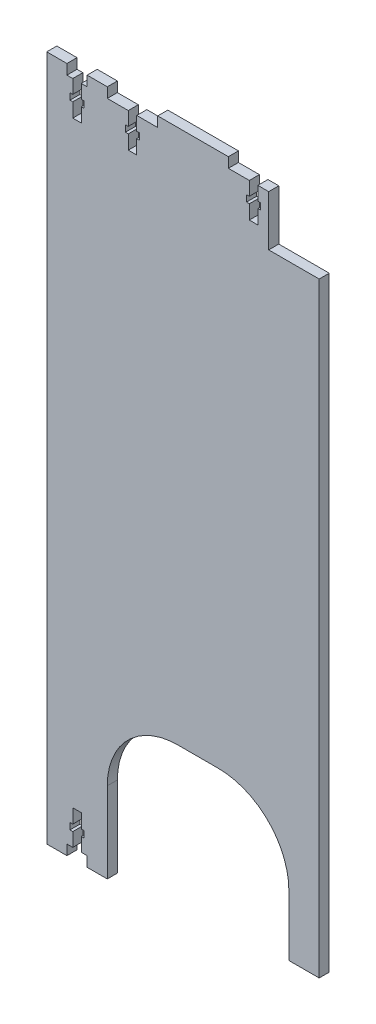
SolidWorks part; units mm, degrees
ref_plane "Front Plane" through (0, 0, 0) normal (0, 0, 1) x (1, 0, 0)
ref_plane "Top Plane" through (0, 0, 0) normal (0, 1, 0) x (1, 0, 0)
ref_plane "Right Plane" through (0, 0, 0) normal (1, 0, 0) x (0, 0, -1)
sketch "Sketch1" plane through (0, 0, 0) normal (0, 0, 1) x (1, 0, 0)
  line L0 (-100, 335) -> (-90, 335) construction
  line L1 (0, 0) -> (-110, 0)
  line L2 (0, 0) -> (0, 330)
  line L3 (0, 330) -> (-110, 330)
  line L4 (-110, 0) -> (-110, 330)
  line L5 (-110, 330) -> (-100, 330)
  line L6 (-110, 330) -> (-110, 335)
  line L7 (-110, 335) -> (-100, 335)
  line L8 (-100, 330) -> (-100, 335)
  line L9 (-90, 330) -> (-80, 330)
  line L10 (-90, 330) -> (-90, 335)
  line L11 (-90, 335) -> (-80, 335)
  line L12 (-80, 330) -> (-80, 335)
  line L13 (-55, 335) -> (-20, 335)
  line L14 (-55, 335) -> (-55, 330)
  line L15 (-55, 330) -> (-20, 330)
  line L16 (-20, 335) -> (-20, 330)
  line L17 (-97.1, 330) -> (-92.9, 330)
  line L18 (-97.1, 330) -> (-97.1, 313)
  line L19 (-97.1, 313) -> (-92.9, 313)
  line L20 (-92.9, 330) -> (-92.9, 313)
  line L21 (-98.5, 323.2) -> (-91.5, 323.2)
  line L22 (-98.5, 323.2) -> (-98.5, 320)
  line L23 (-98.5, 320) -> (-91.5, 320)
  line L24 (-91.5, 323.2) -> (-91.5, 320)
  line L25 (-80, 335) -> (-55, 335) construction
  line L26 (-110, 165) -> (-55, 165) construction
  line L27 (-69.6, 330) -> (-65.4, 330)
  line L28 (-69.6, 330) -> (-69.6, 313)
  line L29 (-69.6, 313) -> (-65.4, 313)
  line L30 (-65.4, 330) -> (-65.4, 313)
  line L31 (-71, 323.2) -> (-64, 323.2)
  line L32 (-71, 323.2) -> (-71, 320)
  line L33 (-71, 320) -> (-64, 320)
  line L34 (-64, 323.2) -> (-64, 320)
  line L35 (-9.6, 330) -> (-5.4, 330)
  line L36 (-9.6, 330) -> (-9.6, 313)
  line L37 (-9.6, 313) -> (-5.4, 313)
  line L38 (-5.4, 330) -> (-5.4, 313)
  line L39 (-11, 323.2) -> (-4, 323.2)
  line L40 (-11, 323.2) -> (-11, 320)
  line L41 (-11, 320) -> (-4, 320)
  line L42 (-4, 323.2) -> (-4, 320)
  line L43 (-80, -5) -> (-55, -5) construction
  line L44 (-100, -5) -> (-90, -5) construction
  line L45 (-4, 6.8) -> (-4, 10)
  line L46 (-11, 10) -> (-4, 10)
  line L47 (-11, 6.8) -> (-11, 10)
  line L48 (-11, 6.8) -> (-4, 6.8)
  line L49 (-5.4, 0) -> (-5.4, 17)
  line L50 (-9.6, 17) -> (-5.4, 17)
  line L51 (-9.6, 0) -> (-9.6, 17)
  line L52 (-9.6, 0) -> (-5.4, 0)
  line L53 (-64, 6.8) -> (-64, 10)
  line L54 (-71, 10) -> (-64, 10)
  line L55 (-71, 6.8) -> (-71, 10)
  line L56 (-71, 6.8) -> (-64, 6.8)
  line L57 (-65.4, 0) -> (-65.4, 17)
  line L58 (-69.6, 17) -> (-65.4, 17)
  line L59 (-69.6, 0) -> (-69.6, 17)
  line L60 (-69.6, 0) -> (-65.4, 0)
  line L61 (-91.5, 6.8) -> (-91.5, 10)
  line L62 (-98.5, 10) -> (-91.5, 10)
  line L63 (-98.5, 6.8) -> (-98.5, 10)
  line L64 (-98.5, 6.8) -> (-91.5, 6.8)
  line L65 (-92.9, 0) -> (-92.9, 17)
  line L66 (-97.1, 17) -> (-92.9, 17)
  line L67 (-97.1, 0) -> (-97.1, 17)
  line L68 (-97.1, 0) -> (-92.9, 0)
  line L69 (-20, -5) -> (-20, 0)
  line L70 (-55, 0) -> (-20, 0)
  line L71 (-55, -5) -> (-55, 0)
  line L72 (-55, -5) -> (-20, -5)
  line L73 (-80, 0) -> (-80, -5)
  line L74 (-90, -5) -> (-80, -5)
  line L75 (-90, 0) -> (-90, -5)
  line L76 (-90, 0) -> (-80, 0)
  line L77 (-100, 0) -> (-100, -5)
  line L78 (-110, -5) -> (-100, -5)
  line L79 (-110, 0) -> (-110, -5)
  line L80 (-110, 0) -> (-100, 0)
  line L81 (0, 0) -> (-110, 0)
  line L82 (-80, 0) -> (-80, 70) construction
  line L83 (-80, 70) -> (0, 70) construction
  line L84 (-80, 35) -> (-45, 35) construction
  line L85 (-80, 35) -> (-80, 0)
  line L86 (-45, 70) -> (0, 70)
  circle A0 centre (-45, 35) radius 35
  point P24 (-95, 335)
  point P25 (-95, 313)
  point P26 (-95, 320)
  point P35 (-67.5, 323.2)
  point P36 (-67.5, 313)
  point P37 (-67.5, 335)
  point P38 (-7.5, 330)
  point P47 (-7.5, 313)
  point P48 (-7.5, 320)
  point P86 (-7.5, 0)
  point P87 (-10, 70)
  dimension "D1" = 110
  dimension "D2" = 330
  dimension "D3" = 5
  dimension "D4" = 10
  dimension "D5" = 10
  dimension "D6" = 10
  dimension "D7" = 5
  dimension "D8" = 35
  dimension "D9" = 25
  dimension "D10" = 5
  dimension "D11" = 7
  dimension "D12" = 3.2
  dimension "D13" = 6.8
  dimension "D14" = 17
  dimension "D15" = 4.2
  dimension "D16" = 17
  dimension "D17" = 3.2
  dimension "D18" = 6.8
  dimension "D19" = 4.2
  dimension "D20" = 7
  dimension "D21" = 12.5
  dimension "D22" = 3.2
  dimension "D23" = 7
  dimension "D24" = 4.2
  dimension "D25" = 70
  dimension "D26" = 70
  dimension "D27" = 35
extrude "Boss-Extrude1" add sketch "Sketch1" along normal blind 5 contours L1 L75 L74 L73 | L1 L79 L78 L77 | A0 L86 L2 L3 L38 L39 L42 L41 L37 L36 L40 L30 L31 L34 L33 L29 L28 L32 L20 L21 L24 L23 L19 L18 L22 L4 L1 L67 L64 L63 | L16 L13 L14 L3 | L3 L12 L11 L10 | L3 L8 L7 L6 | L69 L70 L71 L72
sketch "Sketch2" plane through (0, 0, 5) normal (0, 0, 1) x (1, 0, 0)
  line L1 (-61.0814, 17.0013) -> (-4.5093, 17.0013)
  line L2 (-61.0814, 17.0013) -> (-61.0814, -29.2983)
  line L3 (-61.0814, -29.2983) -> (-4.5093, -29.2983)
  line L4 (-4.5093, 17.0013) -> (-4.5093, -29.2983)
extrude "Cut-Extrude1" cut sketch "Sketch2" against normal blind 10
sketch "Sketch3" plane through (0, 0, 5) normal (0, 0, 1) x (1, 0, 0)
  line L0 (0, 305) -> (25, 305)
  line L1 (0, 70) -> (0, 330) construction
  line L2 (25, 305) -> (25, 70)
  line L3 (0, 305) -> (0, 70)
  line L4 (-9.6, 330) -> (-20, 330) construction
  line L5 (-80, -5) -> (53.0892, -5) construction
  line L6 (10, 35) -> (10, -5)
  line L7 (-25, 70) -> (0, 70)
  line L8 (10, -5) -> (25, -5)
  line L9 (25, -5) -> (25, 70)
  arc A0 (10, 35) -> (-25, 70) centre (-25, 35) ccw
  point P9 (-45, 35)
  point P18 (-25, 70)
  point P20 (10, 35)
  dimension "D2" = 25
  dimension "D3" = 25
  dimension "D1" = 25
extrude "Boss-Extrude2" add sketch "Sketch3" against normal blind 5
sketch "Sketch4" plane through (0, 0, 5) normal (0, 0, 1) x (1, 0, 0)
  line L0 (25, -5) -> (25, 305) construction
  line L1 (10, -5) -> (25, -5)
  line L2 (10, -5) -> (10, 5)
  line L3 (10, 5) -> (25, 5)
  line L4 (25, -5) -> (25, 5)
  dimension "D1" = 10
extrude "Cut-Extrude2" cut sketch "Sketch4" against normal blind 5
